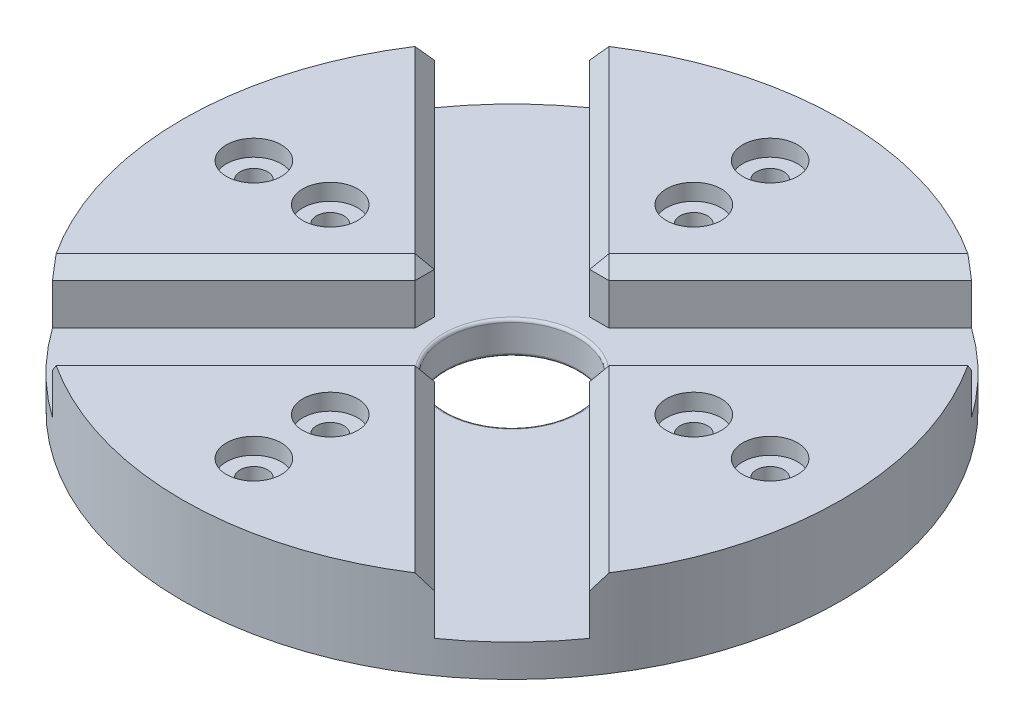
SolidWorks part; units mm, degrees
ref_plane "前视基准面" through (0, 0, 0) normal (0, 0, 1) x (1, 0, 0)
ref_plane "上视基准面" through (0, 0, 0) normal (0, 1, 0) x (1, 0, 0)
ref_plane "右视基准面" through (0, 0, 0) normal (1, 0, 0) x (0, 0, -1)
sketch "草图1" plane through (0, 0, 0) normal (0, 1, 0) x (1, 0, 0)
  line L0 (-8.9, 0) -> (-7.12, 0) construction
  line L1 (-7.12, 0) -> (-6.62, 0) construction
  line L2 (-2.5, -2.5) -> (2.5, 2.5) construction
  line L3 (-2.5, 2.5) -> (0, 0) construction
  line L4 (0, 8.9) -> (0, 7.12) construction
  line L5 (0, 7.12) -> (0, 6.62) construction
  line L6 (8.9, 0) -> (7.12, 0) construction
  line L7 (7.12, 0) -> (6.62, 0) construction
  line L8 (0, -8.9) -> (0, -7.12) construction
  line L9 (0, -7.12) -> (0, -6.62) construction
  circle A0 centre (-9.4, 0) radius 0.5
  circle A1 centre (-6.62, 0) radius 0.5
  circle A2 centre (0, 9.4) radius 0.5
  circle A3 centre (0, 6.62) radius 0.5
  circle A4 centre (9.4, 0) radius 0.5
  circle A5 centre (6.62, 0) radius 0.5
  circle A6 centre (0, -9.4) radius 0.5
  circle A7 centre (0, -6.62) radius 0.5
  circle A8 centre (0, 0) radius 12
extrude "凸台-拉伸1" add sketch "草图1" along normal blind 1.18
sketch "草图2" plane through (0, 1.18, 0) normal (0, 1, 0) x (1, 0, 0)
  line L0 (0, 2.8284) -> (-6.9524, 9.7808)
  line L1 (-2.8284, 0) -> (-9.7808, 6.9524)
  line L2 (-1.4142, -1.4142) -> (-1.4139, -1.4145)
  line L3 (2.8284, 0) -> (9.7808, -6.9524)
  line L4 (2.8284, 0) -> (9.7808, 6.9524)
  line L5 (0.0002, -2.8283) -> (-6.9524, -9.7808)
  line L6 (0, 2.8284) -> (6.9524, 9.7808)
  line L7 (-2.8284, 0) -> (-9.7808, -6.9524)
  line L8 (0.0002, -2.8283) -> (6.9535, -9.78)
  circle A0 centre (0, 0) radius 2 construction
  circle A1 centre (0, 0) radius 12 construction
  arc A2 (-9.7808, 6.9524) -> (-9.7808, -6.9524) centre (0, 0) ccw
  arc A3 (-6.9524, -9.7808) -> (6.9535, -9.78) centre (0, 0) ccw
  arc A4 (9.7808, -6.9524) -> (9.7808, 6.9524) centre (0, 0) ccw
  arc A5 (6.9524, 9.7808) -> (-6.9524, 9.7808) centre (0, 0) ccw
  circle A6 centre (0, -9.4) radius 0.5 construction
  circle A7 centre (6.62, 0) radius 0.5 construction
  circle A8 centre (9.4, 0) radius 0.5 construction
  circle A9 centre (0, -6.62) radius 0.5 construction
  circle A10 centre (-9.4, 0) radius 0.5 construction
  circle A11 centre (-6.62, 0) radius 0.5 construction
  circle A12 centre (0, 9.4) radius 0.5 construction
  circle A13 centre (0, 6.62) radius 0.5 construction
  circle A14 centre (0, -9.4) radius 0.5
  circle A15 centre (6.62, 0) radius 0.5
  circle A16 centre (9.4, 0) radius 0.5
  circle A17 centre (0, -6.62) radius 0.5
  circle A18 centre (-9.4, 0) radius 0.5
  circle A19 centre (-6.62, 0) radius 0.5
  circle A20 centre (0, 9.4) radius 0.5
  circle A21 centre (0, 6.62) radius 0.5
  circle M9 centre (0, -9.4) radius 0.5
  circle M10 centre (9.4, 0) radius 0.5
  circle M11 centre (0, 9.4) radius 0.5
  circle M12 centre (-9.4, 0) radius 0.5
  circle M13 centre (0, 0) radius 12
  circle M14 centre (-6.62, 0) radius 0.5
  circle M15 centre (0, 6.62) radius 0.5
  circle M16 centre (6.62, 0) radius 0.5
  circle M17 centre (0, -6.62) radius 0.5
extrude "凸台-拉伸2" add sketch "草图2" along normal blind 2 contours L7 L1 M13 M14 M12 | L0 L6 M13 M15 M11 | L4 L3 M13 M10 M16 | L8 L5 M13 M17 M9
sketch "草图3" plane through (0, 3.18, 0) normal (0, 1, 0) x (1, 0, 0)
  circle A0 centre (-9.4, 0) radius 1
  circle A1 centre (-6.62, 0) radius 1
  circle A2 centre (0, 9.4) radius 1
  circle A3 centre (0, 6.62) radius 1
  circle A4 centre (9.4, 0) radius 1
  circle A5 centre (6.62, 0) radius 1
  circle A6 centre (0, -9.4) radius 1
  circle A7 centre (0, -6.62) radius 1
  dimension "D1" = 4
extrude "切除-拉伸1" cut sketch "草图3" against normal blind 0.6
chamfer "倒角1" distance 0.5 angle 45 12 edges at (-3.4761, 3.18, 6.3045) (3.4768, 3.18, 6.3042) (0.0002, 2.18, 2.8283) (6.3046, 3.18, 3.4762) (6.3046, 3.18, -3.4762) (2.8284, 2.18, 0) (-3.4762, 3.18, -6.3046) (3.4762, 3.18, -6.3046) (0, 2.18, -2.8284) (-2.8284, 2.18, 0) (-6.3046, 3.18, -3.4762) (-6.3046, 3.18, 3.4762)
sketch "草图4" plane through (0, 1.18, 0) normal (0, 1, 0) x (1, 0, 0)
  circle A0 centre (0, 0) radius 2.4
extrude "切除-拉伸2" cut sketch "草图4" against normal blind 4.6
fillet "圆角1" radius 0.1 2 edges at (0, 0, 2.4) (0, 1.18, 2.4)
